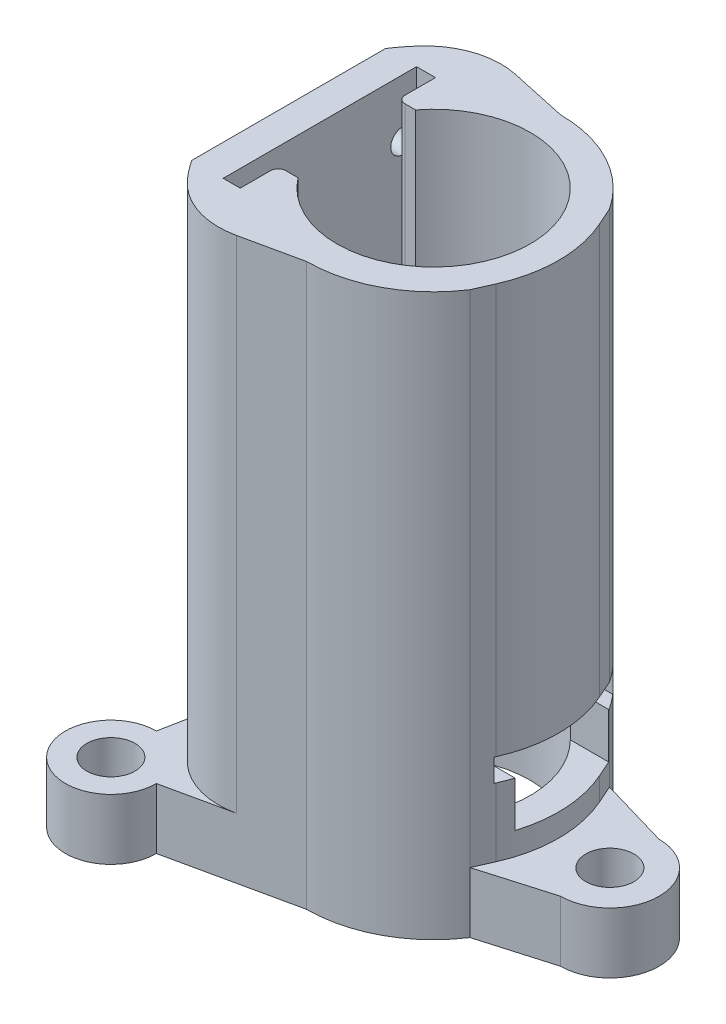
SolidWorks part; units mm, degrees
ref_plane "Front Plane" through (0, 0, 0) normal (0, 0, 1) x (1, 0, 0)
ref_plane "Top Plane" through (0, 0, 0) normal (0, 1, 0) x (1, 0, 0)
ref_plane "Right Plane" through (0, 0, 0) normal (1, 0, 0) x (0, 0, -1)
sketch "Sketch1" plane through (0, 0, 0) normal (0, 1, 0) x (1, 0, 0)
  line L0 (-14.5, 12.5) -> (-22.2782, 20.2782) construction
  line L1 (0, 0) -> (-14.5, 0) construction
  line L2 (0, 0) -> (23.25, 0) construction
  line L3 (0, 0) -> (0, -20.3711) construction
  line L4 (12.75, 0) -> (12.75, -5.8588) construction
  line L5 (0, 16.75) -> (-16.2782, 20.2782)
  line L9 (-22.2782, 14.2782) -> (-19.5, 0)
  line L11 (-14.5, 0) -> (-14.5, 12.5) construction
  line L12 (23.25, 6.5) -> (13.9983, 9.1984)
  line L13 (0, -16.75) -> (-16.2782, -20.2782)
  line L14 (-14.5, -12.5) -> (-22.2782, -20.2782) construction
  line L15 (-22.2782, -14.2782) -> (-19.5, 0)
  line L16 (23.25, -6.5) -> (13.9983, -9.1984)
  circle A1 centre (0, 0) radius 12.75
  arc A4 (0, -16.75) -> (13.9983, -9.1984) centre (0, 0) ccw
  circle A6 centre (0, 0) radius 16.75 construction
  circle A13 centre (23.25, 0) radius 3.175
  arc A16 (23.25, -6.5) -> (23.25, 6.5) centre (23.25, 0) ccw
  circle A17 centre (-22.2782, 20.2782) radius 3.175
  arc A18 (-16.2782, 20.2782) -> (-22.2782, 14.2782) centre (-22.2782, 20.2782) ccw
  arc A19 (13.9983, 9.1984) -> (0, 16.75) centre (0, 0) ccw
  arc A20 (-16.2782, -20.2782) -> (-22.2782, -14.2782) centre (-22.2782, -20.2782) cw
  circle A21 centre (-22.2782, -20.2782) radius 3.175
  dimension "D1" = 4
  dimension "D2" = 25.5
  dimension "D4" = 6.35
  dimension "D5" = 12
  dimension "D6" = 5
  dimension "D3" = 11
  dimension "D11" = 6.35
  dimension "D14" = 13
  dimension "D18" = 14.5
  dimension "D19" = 12.5
extrude "Boss-Extrude2" add sketch "Sketch1" along normal blind 8
sketch "Sketch2" plane through (0, 8, 0) normal (0, 1, 0) x (1, 0, 0)
  line L0 (-16.2782, -20.2782) -> (0, -16.75) construction
  line L2 (-22.2782, 14.2782) -> (-19.5, 0) construction
  line L3 (0, 16.75) -> (-16.2782, 20.2782) construction
  line L4 (-7.6077, -18.3989) -> (0, -16.75)
  line L7 (0, 16.75) -> (-7.6077, 18.3989)
  line L8 (-15, 12.75) -> (-15, -12.75)
  line L9 (0, 0) -> (-15, 0) construction
  line L10 (13.9983, -9.1984) -> (15.0587, -6.8068)
  line L11 (15.0587, 6.8068) -> (13.9983, 9.1984)
  line L12 (-15, 0) -> (-15, 12.75) construction
  line L13 (-15, -12.75) -> (-12.75, -12.75)
  line L14 (-12.75, -12.75) -> (-12.75, -8.75)
  line L15 (-11.75, -7.75) -> (-10.1242, -7.75)
  line L16 (-15, 12.75) -> (-12.5, 12.75)
  line L17 (-12.5, 12.75) -> (-12.5, 8.75)
  line L18 (-11.5, 7.75) -> (-10.1242, 7.75)
  line L19 (-12.5, 8.75) -> (-12.5, 0.25) construction
  line L20 (-15, 12.75) -> (-33.0163, 12.75) construction
  line L21 (-15, -12.75) -> (-33.0163, -12.75) construction
  line L22 (-19.1185, 12.75) -> (-19.1185, -12.75)
  arc A0 (0, -16.75) -> (13.9983, -9.1984) centre (0, 0) ccw construction
  arc A1 (13.9983, 9.1984) -> (0, 16.75) centre (0, 0) ccw construction
  arc A2 (0, -16.75) -> (13.9983, -9.1984) centre (0, 0) ccw
  arc A3 (13.9983, 9.1984) -> (0, 16.75) centre (0, 0) ccw
  arc A4 (15.0587, 6.8068) -> (15.0587, -6.8068) centre (-0.2934, 0) cw
  arc A5 (-18.6558, 13.4522) -> (-17.2075, 15.2611) centre (0, 0) cw
  arc A6 (-18.6558, -13.4522) -> (-17.2075, -15.2611) centre (0, 0) ccw
  arc A7 (-17.2075, 15.2611) -> (-7.6077, 18.3989) centre (-9.726, 8.6258) cw
  arc A8 (-17.2075, -15.2611) -> (-7.6077, -18.3989) centre (-9.726, -8.6258) ccw
  arc A9 (-18.6558, -13.4522) -> (-19.1185, -12.75) centre (-10.5446, -7.6034) cw
  arc A10 (-19.1185, 12.75) -> (-18.6558, 13.4522) centre (-10.5446, 7.6034) cw
  arc A11 (-10.1242, -7.75) -> (-10.1242, 7.75) centre (0, 0) ccw
  arc A12 (-11.75, -7.75) -> (-12.75, -8.75) centre (-11.75, -8.75) ccw
  arc A13 (-12.5, 8.75) -> (-11.5, 7.75) centre (-11.5, 8.75) ccw
  point P22 (-12.3221, 19.4207)
  point P25 (-12.3221, -19.4207)
  point P28 (-20.9489, -9.4943)
  point P31 (-20.9489, 9.4943)
  point P32 (16.5, 0)
  point P42 (-12.75, -7.75)
  point P45 (-12.5, 7.75)
  dimension "D1" = 16.5
  dimension "D4" = 23
  dimension "D5" = 10
  dimension "D6" = 2.6162
  dimension "D12" = 1
  dimension "D2" = 15
  dimension "D3" = 12.75
  dimension "D7" = 2.6162
  dimension "D8" = 25.5
  dimension "D9" = 5
  dimension "D10" = 5
  dimension "D11" = 2.5
  dimension "D13" = 4.1185
extrude "Boss-Extrude3" add sketch "Sketch2" along normal blind 66
sketch "Sketch4" plane through (-19.1185, 0, 0) normal (-1, 0, 0) x (0, 0, 1)
  line L0 (10.95, 74) -> (10.95, 66.47) construction
  line L1 (-12.75, 74) -> (12.75, 74) construction
  line L2 (12.75, 74) -> (12.75, 8) construction
  line L3 (0, 74) -> (0, 31.9249) construction
  line L4 (-10.95, 74) -> (-10.95, 66.47) construction
  line L5 (10.95, 66.47) -> (10.95, 34.72) construction
  circle A0 centre (10.95, 66.47) radius 1.6
  circle A1 centre (-10.95, 66.47) radius 1.6
  circle A2 centre (10.95, 34.72) radius 1.6
  circle A3 centre (-10.95, 34.72) radius 1.6
  dimension "D3" = 3.2
  dimension "D5" = 3.2
  dimension "D1" = 7.53
  dimension "D2" = 1.8
  dimension "D4" = 31.75
extrude "Cut-Extrude1" cut sketch "Sketch4" against normal blind 6
sketch "Sketch5" plane through (-15, 0, 0) normal (1, 0, 0) x (0, 0, -1)
  line L0 (-5, 17) -> (-7, 17)
  line L2 (-5, 17) -> (-5, 11)
  line L3 (-5, 11) -> (0, 11)
  line L5 (0, 8) -> (0, 0) construction
  line L6 (0, 0) -> (-14.2782, 0) construction
  line L7 (-7, 17) -> (-7, 20)
  line L8 (0, 11) -> (0, 31.63) construction
  line L9 (-7, 20) -> (0, 20)
  line L10 (0, 20) -> (11, 20)
  line L11 (11, 20) -> (11, 17)
  line L12 (11, 17) -> (9, 17)
  line L13 (9, 17) -> (9, 11)
  line L14 (9, 11) -> (0, 11)
  point P13 (0, 11)
  point P14 (0, 0)
  dimension "D1" = 6
  dimension "D2" = 5
  dimension "D3" = 3
  dimension "D4" = 11
  dimension "D5" = 2
  dimension "D6" = 9
  dimension "D7" = 6
  dimension "D8" = 2
extrude "Cut-Extrude2" cut sketch "Sketch5" along normal blind 62
sketch "Sketch6" plane through (-15, 0, 0) normal (1, 0, 0) x (0, 0, -1)
  line L0 (11, 20) -> (11, 17)
  line L1 (11, 17) -> (9, 17)
  line L2 (9, 17) -> (9, 11)
  line L3 (9, 11) -> (6.1306, 11)
  line L4 (9, 11) -> (0, 11) construction
  line L5 (6.1306, 11) -> (6.1306, 20)
  line L6 (0, 20) -> (11, 20) construction
  line L7 (6.1306, 20) -> (11, 20)
extrude "Boss-Extrude4" add sketch "Sketch6" along normal blind 10
sketch "Sketch7" plane through (0, 74, 0) normal (0, 1, 0) x (1, 0, 0)
  line L0 (-15, 12.75) -> (-15, 4.5)
  line L1 (-15, 9) -> (-15, 0) construction
  line L2 (-15, 4.5) -> (-3.9977, 4.5)
  line L3 (-3.9977, 4.5) -> (-3.9977, 12.1071)
  line L4 (-15, 12.75) -> (-12.5, 12.75)
  line L5 (-12.5, 12.75) -> (-12.5, 8.75)
  line L6 (-10.1242, 7.75) -> (-11.5, 7.75) construction
  line L7 (-10.1242, 7.75) -> (-11.5, 7.75)
  arc A0 (-10.1242, -7.75) -> (-10.1242, 7.75) centre (0, 0) ccw construction
  arc A1 (-12.5, 8.75) -> (-11.5, 7.75) centre (-11.5, 8.75) ccw construction
  arc A2 (-3.9977, 12.1071) -> (-10.1242, 7.75) centre (0, 0) ccw
  arc A3 (-12.5, 8.75) -> (-11.5, 7.75) centre (-11.5, 8.75) ccw
extrude "Cut-Extrude3" cut sketch "Sketch7" against normal blind 66
